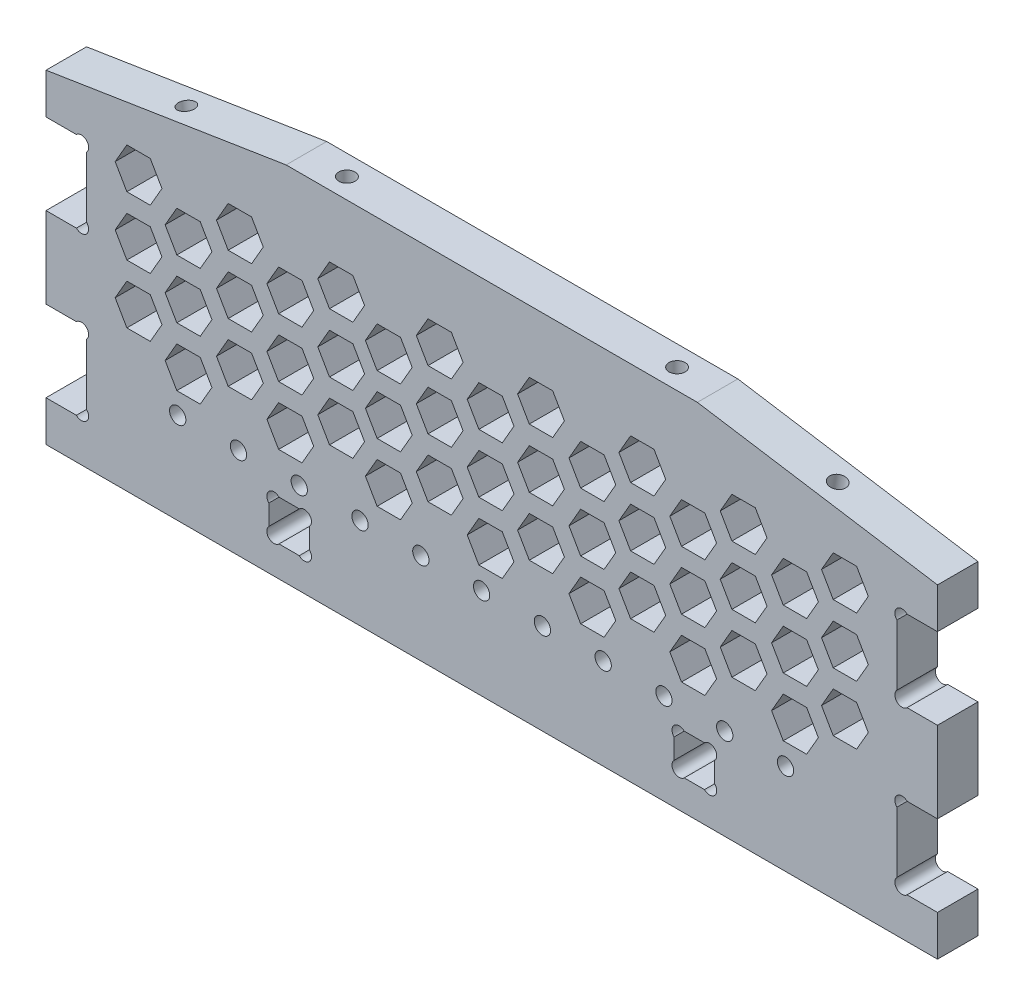
SolidWorks part; units mm, degrees
material "6061 Alloy"
ref_plane "Front" through (0, 0, 0) normal (0, 0, 1) x (1, 0, 0)
ref_plane "Top" through (0, 0, 0) normal (0, 1, 0) x (1, 0, 0)
ref_plane "Right" through (0, 0, 0) normal (1, 0, 0) x (0, 0, -1)
sketch "Sketch2" plane through (0, 0, 0) normal (0, 0, 1) x (1, 0, 0)
  line L1 (-139.7, -50.8) -> (139.7, -50.8)
  line L2 (-139.7, -50.8) -> (-139.7, 50.8)
  line L3 (-139.7, 50.8) -> (139.7, 50.8)
  line L4 (139.7, -50.8) -> (139.7, 50.8)
  line L5 (-139.7, -50.8) -> (139.7, 50.8) construction
  line L6 (-139.7, 50.8) -> (139.7, -50.8) construction
  point P0 (0, 0)
  dimension "D1" = 279.4
  dimension "D2" = 101.6
extrude "Rectangle Extrusion" add sketch "Sketch2" along normal blind 12.7
sketch "Sketch3" plane through (0, 0, 0) normal (0, 0, -1) x (-1, 0, 0)
  line L0 (-139.7, -50.8) -> (-63.5, -50.8) construction
  line L1 (139.7, -50.8) -> (-139.7, -50.8) construction
  line L2 (-63.5, -50.8) -> (-63.5, -34.925) construction
  line L3 (0, 6.985) -> (0, -6.985) construction
  line L4 (-69.85, -41.275) -> (-57.15, -41.275)
  line L5 (-69.85, -41.275) -> (-69.85, -28.575)
  line L6 (-69.85, -28.575) -> (-57.15, -28.575)
  line L7 (-57.15, -41.275) -> (-57.15, -28.575)
  line L8 (-69.85, -41.275) -> (-57.15, -28.575) construction
  line L9 (-69.85, -28.575) -> (-57.15, -41.275) construction
  line L10 (69.85, -28.575) -> (57.15, -28.575)
  line L11 (57.15, -41.275) -> (57.15, -28.575)
  line L12 (69.85, -41.275) -> (57.15, -41.275)
  line L13 (69.85, -41.275) -> (69.85, -28.575)
  line L14 (-69.85, -34.925) -> (-57.15, -34.925) construction
  circle A0 centre (-68.2625, -30.1625) radius 2.2454
  circle A1 centre (-58.7375, -30.1625) radius 2.2454
  circle A2 centre (-58.7375, -39.6875) radius 2.2454
  circle A3 centre (-68.2625, -39.6875) radius 2.2454
  circle A4 centre (58.7375, -39.6875) radius 2.2454
  circle A5 centre (68.2625, -39.6875) radius 2.2454
  circle A6 centre (58.7375, -30.1625) radius 2.2454
  circle A7 centre (68.2625, -30.1625) radius 2.2454
  dimension "D5" = 1.5875
  dimension "D6" = 4.4907
  dimension "D1" = 76.2
  dimension "D2" = 9.525
  dimension "D3" = 12.7
  dimension "D4" = 12.7
extrude "Slotting Holes" cut sketch "Sketch3" against normal up to surface (12.7 mm away) contours L6 A0 L5 | L5 A3 L4 A2 L7 A1 L6 A0 | L5 A0 L6 | A1 L7 L6 | A1 L6 L7 | L7 A2 L4 | L4 A2 L7 | A3 L5 L4 | A3 L4 L5 | L10 A6 L11 | L11 A6 L10 | L13 A7 L10 A6 L11 A4 L12 A5 | A7 L13 L10 | A7 L10 L13 | L12 A5 L13 | A4 L12 L11 | L13 A5 L12 | A4 L11 L12 up to face at (0, 0, 12.7)
sketch "Sketch4" plane through (0, 0, 12.7) normal (0, 0, 1) x (1, 0, 0)
  line L0 (0, -11.43) -> (0, 0) construction
  line L1 (6.9677, 27.5012) -> (3.3015, 33.8512)
  line L2 (-24.9281, 27.5012) -> (-28.5942, 33.8512)
  line L3 (-28.5942, 33.8512) -> (-35.9266, 33.8512)
  line L4 (-35.9266, 33.8512) -> (-39.5928, 27.5012)
  line L5 (-39.5928, 27.5012) -> (-35.9266, 21.1512)
  line L6 (-35.9266, 21.1512) -> (-28.5942, 21.1512)
  line L7 (-28.5942, 21.1512) -> (-24.9281, 27.5012)
  line L8 (3.3015, 33.8512) -> (-4.0309, 33.8512)
  line L9 (-4.0309, 33.8512) -> (-7.697, 27.5012)
  line L10 (-7.697, 27.5012) -> (-4.0309, 21.1512)
  line L11 (-4.0309, 21.1512) -> (3.3015, 21.1512)
  line L12 (3.3015, 21.1512) -> (6.9677, 27.5012)
  line L13 (38.8634, 27.5012) -> (35.1972, 33.8512)
  line L14 (35.1972, 33.8512) -> (27.8648, 33.8512)
  line L15 (27.8648, 33.8512) -> (24.1987, 27.5012)
  line L16 (24.1987, 27.5012) -> (27.8648, 21.1512)
  line L17 (27.8648, 21.1512) -> (35.1972, 21.1512)
  line L18 (35.1972, 21.1512) -> (38.8634, 27.5012)
  line L19 (-8.9802, 18.2937) -> (-12.6464, 24.6437)
  line L20 (-12.6464, 24.6437) -> (-19.9787, 24.6437)
  line L21 (-19.9787, 24.6437) -> (-23.6449, 18.2937)
  line L22 (-23.6449, 18.2937) -> (-19.9787, 11.9437)
  line L23 (-19.9787, 11.9437) -> (-12.6464, 11.9437)
  line L24 (-12.6464, 11.9437) -> (-8.9802, 18.2937)
  line L25 (22.7698, 18.2937) -> (19.1036, 24.6437)
  line L26 (19.1036, 24.6437) -> (11.7713, 24.6437)
  line L27 (11.7713, 24.6437) -> (8.1051, 18.2937)
  line L28 (8.1051, 18.2937) -> (11.7713, 11.9437)
  line L29 (11.7713, 11.9437) -> (19.1036, 11.9437)
  line L30 (19.1036, 11.9437) -> (22.7698, 18.2937)
  line L31 (-24.9281, 9.0862) -> (-28.5942, 15.4362)
  line L32 (-28.5942, 15.4362) -> (-35.9266, 15.4362)
  line L33 (-35.9266, 15.4362) -> (-39.5928, 9.0862)
  line L34 (-39.5928, 9.0862) -> (-35.9266, 2.7362)
  line L35 (-35.9266, 2.7362) -> (-28.5942, 2.7362)
  line L36 (-28.5942, 2.7362) -> (-24.9281, 9.0862)
  line L37 (6.9677, 9.0862) -> (3.3015, 15.4362)
  line L38 (3.3015, 15.4362) -> (-4.0309, 15.4362)
  line L39 (-4.0309, 15.4362) -> (-7.697, 9.0862)
  line L40 (-7.697, 9.0862) -> (-4.0309, 2.7362)
  line L41 (-4.0309, 2.7362) -> (3.3015, 2.7362)
  line L42 (3.3015, 2.7362) -> (6.9677, 9.0862)
  line L43 (38.8634, 9.0862) -> (35.1972, 15.4362)
  line L44 (35.1972, 15.4362) -> (27.8648, 15.4362)
  line L45 (27.8648, 15.4362) -> (24.1987, 9.0862)
  line L46 (24.1987, 9.0862) -> (27.8648, 2.7362)
  line L47 (27.8648, 2.7362) -> (35.1972, 2.7362)
  line L48 (35.1972, 2.7362) -> (38.8634, 9.0862)
  line L49 (-24.9281, -9.3288) -> (-28.5942, -2.9788)
  line L50 (-28.5942, -2.9788) -> (-35.9266, -2.9788)
  line L51 (-35.9266, -2.9788) -> (-39.5928, -9.3288)
  line L52 (-39.5928, -9.3288) -> (-35.9266, -15.6788)
  line L53 (-35.9266, -15.6788) -> (-28.5942, -15.6788)
  line L54 (-28.5942, -15.6788) -> (-24.9281, -9.3288)
  line L55 (-8.9802, -18.5363) -> (-12.6464, -12.1863)
  line L56 (-12.6464, -12.1863) -> (-19.9787, -12.1863)
  line L57 (-19.9787, -12.1863) -> (-23.6449, -18.5363)
  line L58 (-23.6449, -18.5363) -> (-19.9787, -24.8863)
  line L59 (-19.9787, -24.8863) -> (-12.6464, -24.8863)
  line L60 (-12.6464, -24.8863) -> (-8.9802, -18.5363)
  line L61 (6.9677, -9.3288) -> (3.3015, -2.9788)
  line L62 (3.3015, -2.9788) -> (-4.0309, -2.9788)
  line L63 (-4.0309, -2.9788) -> (-7.697, -9.3288)
  line L64 (-7.697, -9.3288) -> (-4.0309, -15.6788)
  line L65 (-4.0309, -15.6788) -> (3.3015, -15.6788)
  line L66 (3.3015, -15.6788) -> (6.9677, -9.3288)
  line L67 (22.7698, -18.5363) -> (19.1036, -12.1863)
  line L68 (19.1036, -12.1863) -> (11.7713, -12.1863)
  line L69 (11.7713, -12.1863) -> (8.1051, -18.5363)
  line L70 (8.1051, -18.5363) -> (11.7713, -24.8863)
  line L71 (11.7713, -24.8863) -> (19.1036, -24.8863)
  line L72 (19.1036, -24.8863) -> (22.7698, -18.5363)
  line L73 (38.8634, -9.3288) -> (35.1972, -2.9788)
  line L74 (35.1972, -2.9788) -> (27.8648, -2.9788)
  line L75 (27.8648, -2.9788) -> (24.1987, -9.3288)
  line L76 (24.1987, -9.3288) -> (27.8648, -15.6788)
  line L77 (27.8648, -15.6788) -> (35.1972, -15.6788)
  line L78 (35.1972, -15.6788) -> (38.8634, -9.3288)
  line L79 (38.8634, -27.7438) -> (35.1972, -21.3938)
  line L80 (35.1972, -21.3938) -> (27.8648, -21.3938)
  line L81 (27.8648, -21.3938) -> (24.1987, -27.7438)
  line L82 (24.1987, -27.7438) -> (27.8648, -34.0938)
  line L83 (27.8648, -34.0938) -> (35.1972, -34.0938)
  line L84 (35.1972, -34.0938) -> (38.8634, -27.7438)
  line L85 (6.9677, -27.7438) -> (3.3015, -21.3938)
  line L86 (-4.0309, -21.3938) -> (-7.697, -27.7438)
  line L87 (-7.697, -27.7438) -> (-4.0309, -34.0938)
  line L88 (-4.0309, -34.0938) -> (3.3015, -34.0938)
  line L89 (3.3015, -34.0938) -> (6.9677, -27.7438)
  line L90 (3.3015, -21.3938) -> (-4.0309, -21.3938)
  line L91 (-24.9281, -27.7438) -> (-28.5942, -21.3938)
  line L92 (-28.5942, -21.3938) -> (-35.9266, -21.3938)
  line L93 (-35.9266, -21.3938) -> (-39.5928, -27.7438)
  line L94 (-39.5928, -27.7438) -> (-35.9266, -34.0938)
  line L95 (-35.9266, -34.0938) -> (-28.5942, -34.0938)
  line L96 (-28.5942, -34.0938) -> (-24.9281, -27.7438)
  line L97 (22.7698, -0.1213) -> (19.1036, 6.2287)
  line L98 (19.1036, 6.2287) -> (11.7713, 6.2287)
  line L99 (11.7713, 6.2287) -> (8.1051, -0.1213)
  line L100 (8.1051, -0.1213) -> (11.7713, -6.4713)
  line L101 (11.7713, -6.4713) -> (19.1036, -6.4713)
  line L102 (19.1036, -6.4713) -> (22.7698, -0.1213)
  line L103 (-8.9802, -0.1213) -> (-12.6464, 6.2287)
  line L104 (-12.6464, 6.2287) -> (-19.9787, 6.2287)
  line L105 (-19.9787, 6.2287) -> (-23.6449, -0.1213)
  line L106 (-23.6449, -0.1213) -> (-19.9787, -6.4713)
  line L107 (-19.9787, -6.4713) -> (-12.6464, -6.4713)
  line L108 (-12.6464, -6.4713) -> (-8.9802, -0.1213)
  line L109 (-8.9802, -37.0783) -> (-12.6464, -30.7283)
  line L110 (-12.6464, -30.7283) -> (-19.9787, -30.7283)
  line L111 (-19.9787, -30.7283) -> (-23.6449, -37.0783)
  line L112 (-23.6449, -37.0783) -> (-19.9787, -43.4283)
  line L113 (-19.9787, -43.4283) -> (-12.6464, -43.4283)
  line L114 (-12.6464, -43.4283) -> (-8.9802, -37.0783)
  line L115 (22.7698, -37.0783) -> (19.1036, -30.7283)
  line L116 (19.1036, -30.7283) -> (11.7713, -30.7283)
  line L117 (11.7713, -30.7283) -> (8.1051, -37.0783)
  line L118 (8.1051, -37.0783) -> (11.7713, -43.4283)
  line L119 (11.7713, -43.4283) -> (19.1036, -43.4283)
  line L120 (19.1036, -43.4283) -> (22.7698, -37.0783)
  line L121 (-8.9802, 36.8357) -> (-12.6464, 43.1857)
  line L122 (-12.6464, 43.1857) -> (-19.9787, 43.1857)
  line L123 (-19.9787, 43.1857) -> (-23.6449, 36.8357)
  line L124 (-23.6449, 36.8357) -> (-19.9787, 30.4857)
  line L125 (-19.9787, 30.4857) -> (-12.6464, 30.4857)
  line L126 (-12.6464, 30.4857) -> (-8.9802, 36.8357)
  line L127 (22.7698, 36.8357) -> (19.1036, 43.1857)
  line L128 (19.1036, 43.1857) -> (11.7713, 43.1857)
  line L129 (11.7713, 43.1857) -> (8.1051, 36.8357)
  line L130 (8.1051, 36.8357) -> (11.7713, 30.4857)
  line L131 (11.7713, 30.4857) -> (19.1036, 30.4857)
  line L132 (19.1036, 30.4857) -> (22.7698, 36.8357)
  line L133 (63.5, -11.43) -> (63.5, 0) construction
  line L134 (70.4677, 27.5012) -> (66.8015, 33.8512)
  line L141 (66.8015, 33.8512) -> (59.4691, 33.8512)
  line L142 (59.4691, 33.8512) -> (55.803, 27.5012)
  line L143 (55.803, 27.5012) -> (59.4691, 21.1512)
  line L144 (59.4691, 21.1512) -> (66.8015, 21.1512)
  line L145 (66.8015, 21.1512) -> (70.4677, 27.5012)
  line L146 (102.3634, 27.5012) -> (98.6972, 33.8512)
  line L147 (98.6972, 33.8512) -> (91.3648, 33.8512)
  line L148 (91.3648, 33.8512) -> (87.6987, 27.5012)
  line L149 (87.6987, 27.5012) -> (91.3648, 21.1512)
  line L150 (91.3648, 21.1512) -> (98.6972, 21.1512)
  line L151 (98.6972, 21.1512) -> (102.3634, 27.5012)
  line L152 (54.5198, 18.2937) -> (50.8536, 24.6437)
  line L153 (50.8536, 24.6437) -> (43.5213, 24.6437)
  line L154 (43.5213, 24.6437) -> (39.8551, 18.2937)
  line L155 (39.8551, 18.2937) -> (43.5213, 11.9437)
  line L156 (43.5213, 11.9437) -> (50.8536, 11.9437)
  line L157 (50.8536, 11.9437) -> (54.5198, 18.2937)
  line L158 (86.2698, 18.2937) -> (82.6036, 24.6437)
  line L159 (82.6036, 24.6437) -> (75.2713, 24.6437)
  line L160 (75.2713, 24.6437) -> (71.6051, 18.2937)
  line L161 (71.6051, 18.2937) -> (75.2713, 11.9437)
  line L162 (75.2713, 11.9437) -> (82.6036, 11.9437)
  line L163 (82.6036, 11.9437) -> (86.2698, 18.2937)
  line L170 (70.4677, 9.0862) -> (66.8015, 15.4362)
  line L171 (66.8015, 15.4362) -> (59.4691, 15.4362)
  line L172 (59.4691, 15.4362) -> (55.803, 9.0862)
  line L173 (55.803, 9.0862) -> (59.4691, 2.7362)
  line L174 (59.4691, 2.7362) -> (66.8015, 2.7362)
  line L175 (66.8015, 2.7362) -> (70.4677, 9.0862)
  line L176 (102.3634, 9.0862) -> (98.6972, 15.4362)
  line L177 (98.6972, 15.4362) -> (91.3648, 15.4362)
  line L178 (91.3648, 15.4362) -> (87.6987, 9.0862)
  line L179 (87.6987, 9.0862) -> (91.3648, 2.7362)
  line L180 (91.3648, 2.7362) -> (98.6972, 2.7362)
  line L181 (98.6972, 2.7362) -> (102.3634, 9.0862)
  line L188 (54.5198, -18.5363) -> (50.8536, -12.1863)
  line L189 (50.8536, -12.1863) -> (43.5213, -12.1863)
  line L190 (43.5213, -12.1863) -> (39.8551, -18.5363)
  line L191 (39.8551, -18.5363) -> (43.5213, -24.8863)
  line L192 (43.5213, -24.8863) -> (50.8536, -24.8863)
  line L193 (50.8536, -24.8863) -> (54.5198, -18.5363)
  line L194 (70.4677, -9.3288) -> (66.8015, -2.9788)
  line L195 (66.8015, -2.9788) -> (59.4691, -2.9788)
  line L196 (59.4691, -2.9788) -> (55.803, -9.3288)
  line L197 (55.803, -9.3288) -> (59.4691, -15.6788)
  line L198 (59.4691, -15.6788) -> (66.8015, -15.6788)
  line L199 (66.8015, -15.6788) -> (70.4677, -9.3288)
  line L200 (86.2698, -18.5363) -> (82.6036, -12.1863)
  line L201 (82.6036, -12.1863) -> (75.2713, -12.1863)
  line L202 (75.2713, -12.1863) -> (71.6051, -18.5363)
  line L203 (71.6051, -18.5363) -> (75.2713, -24.8863)
  line L204 (75.2713, -24.8863) -> (82.6036, -24.8863)
  line L205 (82.6036, -24.8863) -> (86.2698, -18.5363)
  line L206 (102.3634, -9.3288) -> (98.6972, -2.9788)
  line L207 (98.6972, -2.9788) -> (91.3648, -2.9788)
  line L208 (91.3648, -2.9788) -> (87.6987, -9.3288)
  line L209 (87.6987, -9.3288) -> (91.3648, -15.6788)
  line L210 (91.3648, -15.6788) -> (98.6972, -15.6788)
  line L211 (98.6972, -15.6788) -> (102.3634, -9.3288)
  line L212 (102.3634, -27.7438) -> (98.6972, -21.3938)
  line L213 (98.6972, -21.3938) -> (91.3648, -21.3938)
  line L214 (91.3648, -21.3938) -> (87.6987, -27.7438)
  line L215 (87.6987, -27.7438) -> (91.3648, -34.0938)
  line L216 (91.3648, -34.0938) -> (98.6972, -34.0938)
  line L217 (98.6972, -34.0938) -> (102.3634, -27.7438)
  line L230 (86.2698, -0.1213) -> (82.6036, 6.2287)
  line L231 (82.6036, 6.2287) -> (75.2713, 6.2287)
  line L232 (75.2713, 6.2287) -> (71.6051, -0.1213)
  line L233 (71.6051, -0.1213) -> (75.2713, -6.4713)
  line L234 (75.2713, -6.4713) -> (82.6036, -6.4713)
  line L235 (82.6036, -6.4713) -> (86.2698, -0.1213)
  line L236 (54.5198, -0.1213) -> (50.8536, 6.2287)
  line L237 (50.8536, 6.2287) -> (43.5213, 6.2287)
  line L238 (43.5213, 6.2287) -> (39.8551, -0.1213)
  line L239 (39.8551, -0.1213) -> (43.5213, -6.4713)
  line L240 (43.5213, -6.4713) -> (50.8536, -6.4713)
  line L241 (50.8536, -6.4713) -> (54.5198, -0.1213)
  line L254 (54.5198, 36.8357) -> (50.8536, 43.1857)
  line L255 (50.8536, 43.1857) -> (43.5213, 43.1857)
  line L256 (43.5213, 43.1857) -> (39.8551, 36.8357)
  line L257 (39.8551, 36.8357) -> (43.5213, 30.4857)
  line L258 (43.5213, 30.4857) -> (50.8536, 30.4857)
  line L259 (50.8536, 30.4857) -> (54.5198, 36.8357)
  line L260 (86.2698, 36.8357) -> (82.6036, 43.1857)
  line L261 (82.6036, 43.1857) -> (75.2713, 43.1857)
  line L262 (75.2713, 43.1857) -> (71.6051, 36.8357)
  line L263 (71.6051, 36.8357) -> (75.2713, 30.4857)
  line L264 (75.2713, 30.4857) -> (82.6036, 30.4857)
  line L265 (82.6036, 30.4857) -> (86.2698, 36.8357)
  line L266 (118.0198, 36.8357) -> (114.3536, 43.1857)
  line L267 (114.3536, 43.1857) -> (107.0213, 43.1857)
  line L268 (107.0213, 43.1857) -> (103.3551, 36.8357)
  line L269 (103.3551, 36.8357) -> (107.0213, 30.4857)
  line L270 (107.0213, 30.4857) -> (114.3536, 30.4857)
  line L271 (114.3536, 30.4857) -> (118.0198, 36.8357)
  line L272 (118.0198, 18.2937) -> (114.3536, 24.6437)
  line L273 (114.3536, 24.6437) -> (107.0213, 24.6437)
  line L274 (107.0213, 24.6437) -> (103.3551, 18.2937)
  line L275 (103.3551, 18.2937) -> (107.0213, 11.9437)
  line L276 (107.0213, 11.9437) -> (114.3536, 11.9437)
  line L277 (114.3536, 11.9437) -> (118.0198, 18.2937)
  line L278 (118.0198, -0.1213) -> (114.3536, 6.2287)
  line L279 (114.3536, 6.2287) -> (107.0213, 6.2287)
  line L280 (107.0213, 6.2287) -> (103.3551, -0.1213)
  line L281 (103.3551, -0.1213) -> (107.0213, -6.4713)
  line L282 (107.0213, -6.4713) -> (114.3536, -6.4713)
  line L283 (114.3536, -6.4713) -> (118.0198, -0.1213)
  line L284 (118.0198, -18.5363) -> (114.3536, -12.1863)
  line L285 (114.3536, -12.1863) -> (107.0213, -12.1863)
  line L286 (107.0213, -12.1863) -> (103.3551, -18.5363)
  line L287 (103.3551, -18.5363) -> (107.0213, -24.8863)
  line L288 (107.0213, -24.8863) -> (114.3536, -24.8863)
  line L289 (114.3536, -24.8863) -> (118.0198, -18.5363)
  line L290 (117.8959, -37.2022) -> (114.2298, -30.8522)
  line L291 (114.2298, -30.8522) -> (106.8974, -30.8522)
  line L292 (106.8974, -30.8522) -> (103.2312, -37.2022)
  line L293 (103.2312, -37.2022) -> (106.8974, -43.5522)
  line L294 (106.8974, -43.5522) -> (114.2298, -43.5522)
  line L295 (114.2298, -43.5522) -> (117.8959, -37.2022)
  line L296 (0, -6.985) -> (0, 6.985) construction
  line L297 (-63.5, -11.43) -> (-63.5, 0) construction
  line L298 (-114.2298, -43.5522) -> (-117.8959, -37.2022)
  line L299 (-106.8974, -43.5522) -> (-114.2298, -43.5522)
  line L300 (-103.2312, -37.2022) -> (-106.8974, -43.5522)
  line L301 (-106.8974, -30.8522) -> (-103.2312, -37.2022)
  line L302 (-114.2298, -30.8522) -> (-106.8974, -30.8522)
  line L303 (-117.8959, -37.2022) -> (-114.2298, -30.8522)
  line L304 (-114.3536, -24.8863) -> (-118.0198, -18.5363)
  line L305 (-107.0213, -24.8863) -> (-114.3536, -24.8863)
  line L306 (-103.3551, -18.5363) -> (-107.0213, -24.8863)
  line L307 (-107.0213, -12.1863) -> (-103.3551, -18.5363)
  line L308 (-114.3536, -12.1863) -> (-107.0213, -12.1863)
  line L309 (-118.0198, -18.5363) -> (-114.3536, -12.1863)
  line L310 (-114.3536, -6.4713) -> (-118.0198, -0.1213)
  line L311 (-107.0213, -6.4713) -> (-114.3536, -6.4713)
  line L312 (-103.3551, -0.1213) -> (-107.0213, -6.4713)
  line L313 (-107.0213, 6.2287) -> (-103.3551, -0.1213)
  line L314 (-114.3536, 6.2287) -> (-107.0213, 6.2287)
  line L315 (-118.0198, -0.1213) -> (-114.3536, 6.2287)
  line L316 (-114.3536, 11.9437) -> (-118.0198, 18.2937)
  line L317 (-107.0213, 11.9437) -> (-114.3536, 11.9437)
  line L318 (-103.3551, 18.2937) -> (-107.0213, 11.9437)
  line L319 (-107.0213, 24.6437) -> (-103.3551, 18.2937)
  line L320 (-114.3536, 24.6437) -> (-107.0213, 24.6437)
  line L321 (-118.0198, 18.2937) -> (-114.3536, 24.6437)
  line L322 (-114.3536, 30.4857) -> (-118.0198, 36.8357)
  line L323 (-107.0213, 30.4857) -> (-114.3536, 30.4857)
  line L324 (-103.3551, 36.8357) -> (-107.0213, 30.4857)
  line L325 (-107.0213, 43.1857) -> (-103.3551, 36.8357)
  line L326 (-114.3536, 43.1857) -> (-107.0213, 43.1857)
  line L327 (-118.0198, 36.8357) -> (-114.3536, 43.1857)
  line L328 (-82.6036, 30.4857) -> (-86.2698, 36.8357)
  line L329 (-75.2713, 30.4857) -> (-82.6036, 30.4857)
  line L330 (-71.6051, 36.8357) -> (-75.2713, 30.4857)
  line L331 (-75.2713, 43.1857) -> (-71.6051, 36.8357)
  line L332 (-82.6036, 43.1857) -> (-75.2713, 43.1857)
  line L333 (-86.2698, 36.8357) -> (-82.6036, 43.1857)
  line L334 (-50.8536, 30.4857) -> (-54.5198, 36.8357)
  line L335 (-43.5213, 30.4857) -> (-50.8536, 30.4857)
  line L336 (-39.8551, 36.8357) -> (-43.5213, 30.4857)
  line L337 (-43.5213, 43.1857) -> (-39.8551, 36.8357)
  line L338 (-50.8536, 43.1857) -> (-43.5213, 43.1857)
  line L339 (-54.5198, 36.8357) -> (-50.8536, 43.1857)
  line L346 (-50.8536, -6.4713) -> (-54.5198, -0.1213)
  line L347 (-43.5213, -6.4713) -> (-50.8536, -6.4713)
  line L348 (-39.8551, -0.1213) -> (-43.5213, -6.4713)
  line L349 (-43.5213, 6.2287) -> (-39.8551, -0.1213)
  line L350 (-50.8536, 6.2287) -> (-43.5213, 6.2287)
  line L351 (-54.5198, -0.1213) -> (-50.8536, 6.2287)
  line L352 (-82.6036, -6.4713) -> (-86.2698, -0.1213)
  line L353 (-75.2713, -6.4713) -> (-82.6036, -6.4713)
  line L354 (-71.6051, -0.1213) -> (-75.2713, -6.4713)
  line L355 (-75.2713, 6.2287) -> (-71.6051, -0.1213)
  line L356 (-82.6036, 6.2287) -> (-75.2713, 6.2287)
  line L357 (-86.2698, -0.1213) -> (-82.6036, 6.2287)
  line L358 (-98.6972, -34.0938) -> (-102.3634, -27.7438)
  line L359 (-91.3648, -34.0938) -> (-98.6972, -34.0938)
  line L360 (-87.6987, -27.7438) -> (-91.3648, -34.0938)
  line L361 (-91.3648, -21.3938) -> (-87.6987, -27.7438)
  line L362 (-98.6972, -21.3938) -> (-91.3648, -21.3938)
  line L363 (-102.3634, -27.7438) -> (-98.6972, -21.3938)
  line L364 (-98.6972, -15.6788) -> (-102.3634, -9.3288)
  line L365 (-91.3648, -15.6788) -> (-98.6972, -15.6788)
  line L366 (-87.6987, -9.3288) -> (-91.3648, -15.6788)
  line L367 (-91.3648, -2.9788) -> (-87.6987, -9.3288)
  line L368 (-98.6972, -2.9788) -> (-91.3648, -2.9788)
  line L369 (-102.3634, -9.3288) -> (-98.6972, -2.9788)
  line L370 (-82.6036, -24.8863) -> (-86.2698, -18.5363)
  line L371 (-75.2713, -24.8863) -> (-82.6036, -24.8863)
  line L372 (-71.6051, -18.5363) -> (-75.2713, -24.8863)
  line L373 (-75.2713, -12.1863) -> (-71.6051, -18.5363)
  line L374 (-82.6036, -12.1863) -> (-75.2713, -12.1863)
  line L375 (-86.2698, -18.5363) -> (-82.6036, -12.1863)
  line L376 (-66.8015, -15.6788) -> (-70.4677, -9.3288)
  line L377 (-59.4691, -15.6788) -> (-66.8015, -15.6788)
  line L378 (-55.803, -9.3288) -> (-59.4691, -15.6788)
  line L379 (-59.4691, -2.9788) -> (-55.803, -9.3288)
  line L380 (-66.8015, -2.9788) -> (-59.4691, -2.9788)
  line L381 (-70.4677, -9.3288) -> (-66.8015, -2.9788)
  line L382 (-50.8536, -24.8863) -> (-54.5198, -18.5363)
  line L383 (-43.5213, -24.8863) -> (-50.8536, -24.8863)
  line L384 (-39.8551, -18.5363) -> (-43.5213, -24.8863)
  line L385 (-43.5213, -12.1863) -> (-39.8551, -18.5363)
  line L386 (-50.8536, -12.1863) -> (-43.5213, -12.1863)
  line L387 (-54.5198, -18.5363) -> (-50.8536, -12.1863)
  line L388 (-98.6972, 2.7362) -> (-102.3634, 9.0862)
  line L389 (-91.3648, 2.7362) -> (-98.6972, 2.7362)
  line L390 (-87.6987, 9.0862) -> (-91.3648, 2.7362)
  line L391 (-91.3648, 15.4362) -> (-87.6987, 9.0862)
  line L392 (-98.6972, 15.4362) -> (-91.3648, 15.4362)
  line L393 (-102.3634, 9.0862) -> (-98.6972, 15.4362)
  line L394 (-66.8015, 2.7362) -> (-70.4677, 9.0862)
  line L395 (-59.4691, 2.7362) -> (-66.8015, 2.7362)
  line L396 (-55.803, 9.0862) -> (-59.4691, 2.7362)
  line L397 (-59.4691, 15.4362) -> (-55.803, 9.0862)
  line L398 (-66.8015, 15.4362) -> (-59.4691, 15.4362)
  line L399 (-70.4677, 9.0862) -> (-66.8015, 15.4362)
  line L400 (-82.6036, 11.9437) -> (-86.2698, 18.2937)
  line L401 (-75.2713, 11.9437) -> (-82.6036, 11.9437)
  line L402 (-71.6051, 18.2937) -> (-75.2713, 11.9437)
  line L403 (-75.2713, 24.6437) -> (-71.6051, 18.2937)
  line L404 (-82.6036, 24.6437) -> (-75.2713, 24.6437)
  line L405 (-86.2698, 18.2937) -> (-82.6036, 24.6437)
  line L406 (-50.8536, 11.9437) -> (-54.5198, 18.2937)
  line L407 (-43.5213, 11.9437) -> (-50.8536, 11.9437)
  line L408 (-39.8551, 18.2937) -> (-43.5213, 11.9437)
  line L409 (-43.5213, 24.6437) -> (-39.8551, 18.2937)
  line L410 (-50.8536, 24.6437) -> (-43.5213, 24.6437)
  line L411 (-54.5198, 18.2937) -> (-50.8536, 24.6437)
  line L412 (-98.6972, 21.1512) -> (-102.3634, 27.5012)
  line L413 (-91.3648, 21.1512) -> (-98.6972, 21.1512)
  line L414 (-87.6987, 27.5012) -> (-91.3648, 21.1512)
  line L415 (-91.3648, 33.8512) -> (-87.6987, 27.5012)
  line L416 (-98.6972, 33.8512) -> (-91.3648, 33.8512)
  line L417 (-102.3634, 27.5012) -> (-98.6972, 33.8512)
  line L418 (-66.8015, 21.1512) -> (-70.4677, 27.5012)
  line L419 (-59.4691, 21.1512) -> (-66.8015, 21.1512)
  line L420 (-55.803, 27.5012) -> (-59.4691, 21.1512)
  line L421 (-59.4691, 33.8512) -> (-55.803, 27.5012)
  line L422 (-66.8015, 33.8512) -> (-59.4691, 33.8512)
  line L423 (-70.4677, 27.5012) -> (-66.8015, 33.8512)
  circle A0 centre (-32.2604, 27.5012) radius 6.35 construction
  circle A1 centre (-0.3647, 27.5012) radius 6.35 construction
  circle A2 centre (31.531, 27.5012) radius 6.35 construction
  circle A3 centre (-16.3126, 18.2937) radius 6.35 construction
  circle A4 centre (15.4374, 18.2937) radius 6.35 construction
  circle A5 centre (-32.2604, 9.0862) radius 6.35 construction
  circle A6 centre (-0.3647, 9.0862) radius 6.35 construction
  circle A7 centre (31.531, 9.0862) radius 6.35 construction
  circle A8 centre (-32.2604, -9.3288) radius 6.35 construction
  circle A9 centre (-16.3126, -18.5363) radius 6.35 construction
  circle A10 centre (-0.3647, -9.3288) radius 6.35 construction
  circle A11 centre (15.4374, -18.5363) radius 6.35 construction
  circle A12 centre (31.531, -9.3288) radius 6.35 construction
  circle A13 centre (31.531, -27.7438) radius 6.35 construction
  circle A14 centre (-0.3647, -27.7438) radius 6.35 construction
  circle A15 centre (-32.2604, -27.7438) radius 6.35 construction
  circle A16 centre (-16.3126, -0.1213) radius 6.35 construction
  circle A17 centre (15.4374, -0.1213) radius 6.35 construction
  circle A18 centre (-16.3126, -37.0783) radius 6.35 construction
  circle A19 centre (15.4374, -37.0783) radius 6.35 construction
  circle A20 centre (-16.3126, 36.8357) radius 6.35 construction
  circle A21 centre (15.4374, 36.8357) radius 6.35 construction
  circle A23 centre (63.1353, 27.5012) radius 6.35 construction
  circle A24 centre (95.031, 27.5012) radius 6.35 construction
  circle A25 centre (47.1874, 18.2937) radius 6.35 construction
  circle A26 centre (78.9374, 18.2937) radius 6.35 construction
  circle A28 centre (63.1353, 9.0862) radius 6.35 construction
  circle A29 centre (95.031, 9.0862) radius 6.35 construction
  circle A31 centre (47.1874, -18.5363) radius 6.35 construction
  circle A32 centre (63.1353, -9.3288) radius 6.35 construction
  circle A33 centre (78.9374, -18.5363) radius 6.35 construction
  circle A34 centre (95.031, -9.3288) radius 6.35 construction
  circle A35 centre (95.031, -27.7438) radius 6.35 construction
  circle A38 centre (47.1874, -0.1213) radius 6.35 construction
  circle A39 centre (78.9374, -0.1213) radius 6.35 construction
  circle A42 centre (47.1874, 36.8357) radius 6.35 construction
  circle A43 centre (78.9374, 36.8357) radius 6.35 construction
  circle A44 centre (110.6874, 36.8357) radius 6.35 construction
  circle A45 centre (110.6874, 18.2937) radius 6.35 construction
  circle A46 centre (110.6874, -0.1213) radius 6.35 construction
  circle A47 centre (110.6874, -18.5363) radius 6.35 construction
  circle A48 centre (110.6874, -37.0783) radius 6.35 construction
  circle A49 centre (-110.6874, -37.0783) radius 6.35 construction
  circle A50 centre (-110.6874, -18.5363) radius 6.35 construction
  circle A51 centre (-110.6874, -0.1213) radius 6.35 construction
  circle A52 centre (-110.6874, 18.2937) radius 6.35 construction
  circle A53 centre (-110.6874, 36.8357) radius 6.35 construction
  circle A54 centre (-78.9374, 36.8357) radius 6.35 construction
  circle A55 centre (-47.1874, 36.8357) radius 6.35 construction
  circle A57 centre (-78.9374, -0.1213) radius 6.35 construction
  circle A58 centre (-47.1874, -0.1213) radius 6.35 construction
  circle A59 centre (-95.031, -27.7438) radius 6.35 construction
  circle A60 centre (-95.031, -9.3288) radius 6.35 construction
  circle A61 centre (-78.9374, -18.5363) radius 6.35 construction
  circle A62 centre (-63.1353, -9.3288) radius 6.35 construction
  circle A63 centre (-47.1874, -18.5363) radius 6.35 construction
  circle A64 centre (-95.031, 9.0862) radius 6.35 construction
  circle A65 centre (-63.1353, 9.0862) radius 6.35 construction
  circle A66 centre (-78.9374, 18.2937) radius 6.35 construction
  circle A67 centre (-47.1874, 18.2937) radius 6.35 construction
  circle A68 centre (-95.031, 27.5012) radius 6.35 construction
  circle A69 centre (-63.1353, 27.5012) radius 6.35 construction
  dimension "D1" = 11.43
  dimension "D4" = 11.43
  dimension "D5" = 2
  dimension "D2" = 2
  dimension "D3" = 2
extrude "Honeycomb Pocketing" cut sketch "Sketch4" against normal up to surface (12.7 mm away) contours L327 L322 L323 L324 L325 L326 | L333 L328 L329 L330 L331 L332 | L339 L334 L335 L336 L337 L338 | L125 L126 L121 L122 L123 L124 | L131 L132 L127 L128 L129 L130 | L258 L259 L254 L255 L256 L257 | L264 L265 L260 L261 L262 L263 | L270 L271 L266 L267 L268 L269 | L150 L151 L146 L147 L148 L149 | L144 L145 L134 L141 L142 L143 | L17 L18 L13 L14 L15 L16 | L11 L12 L1 L8 L9 L10 | L6 L7 L2 L3 L4 L5 | L423 L418 L419 L420 L421 L422 | L417 L412 L413 L414 L415 L416 | L321 L316 L317 L318 L319 L320 | L405 L400 L401 L402 L403 L404 | L411 L406 L407 L408 L409 L410 | L23 L24 L19 L20 L21 L22 | L29 L30 L25 L26 L27 L28 | L156 L157 L152 L153 L154 L155 | L162 L163 L158 L159 L160 L161 | L276 L277 L272 L273 L274 L275 | L180 L181 L176 L177 L178 L179 | L174 L175 L170 L171 L172 L173 | L47 L48 L43 L44 L45 L46 | L41 L42 L37 L38 L39 L40 | L35 L36 L31 L32 L33 L34 | L399 L394 L395 L396 L397 L398 | L393 L388 L389 L390 L391 L392 | L315 L310 L311 L312 L313 L314 | L357 L352 L353 L354 L355 L356 | L351 L346 L347 L348 L349 L350 | L107 L108 L103 L104 L105 L106 | L101 L102 L97 L98 L99 L100 | L240 L241 L236 L237 L238 L239 | L234 L235 L230 L231 L232 L233 | L282 L283 L278 L279 L280 L281 | L381 L376 L377 L378 L379 L380 | L53 L54 L49 L50 L51 L52 | L369 L364 L365 L366 L367 L368 | L65 L66 L61 L62 L63 L64 | L77 L78 L73 L74 L75 L76 | L198 L199 L194 L195 L196 L197 | L210 L211 L206 L207 L208 L209 up to face at (-63.5, -34.925, 0)
sketch "Sketch5" plane through (0, 0, 12.7) normal (0, 0, 1) x (1, 0, 0)
  line L0 (139.7, 0) -> (139.7, 50.8) construction
  line L1 (139.7, -50.8) -> (139.7, 50.8) construction
  line L2 (139.7, 0) -> (-139.7, 0) construction
  line L4 (139.7, 25.4) -> (139.7, 38.1)
  line L5 (139.7, 38.1) -> (127, 38.1)
  line L6 (127, 25.4) -> (127, 38.1)
  line L8 (127, 25.4) -> (127, 12.7)
  line L9 (127, 12.7) -> (139.7, 12.7)
  line L10 (139.7, 25.4) -> (139.7, 12.7)
  line L11 (-139.7, 50.8) -> (-139.7, -50.8) construction
  line L12 (127, -12.7) -> (139.7, -12.7)
  line L13 (139.7, -25.4) -> (139.7, -12.7)
  line L14 (127, -25.4) -> (139.7, -25.4)
  line L15 (127, -25.4) -> (127, -12.7)
  line L16 (139.7, -38.1) -> (127, -38.1)
  line L17 (127, -25.4) -> (127, -38.1)
  line L18 (139.7, -25.4) -> (127, -25.4)
  line L19 (139.7, -25.4) -> (139.7, -38.1)
  line L20 (0, 50.8) -> (0, -50.8) construction
  line L21 (139.7, 50.8) -> (-139.7, 50.8) construction
  line L22 (-139.7, -50.8) -> (139.7, -50.8) construction
  line L23 (-139.7, -25.4) -> (-139.7, -38.1)
  line L24 (-139.7, -38.1) -> (-127, -38.1)
  line L25 (-127, -25.4) -> (-127, -38.1)
  line L26 (-127, -25.4) -> (-139.7, -25.4)
  line L27 (-139.7, -25.4) -> (-139.7, -12.7)
  line L28 (-127, -12.7) -> (-139.7, -12.7)
  line L29 (-127, -25.4) -> (-127, -12.7)
  line L30 (-139.7, 38.1) -> (-127, 38.1)
  line L31 (-127, 25.4) -> (-127, 38.1)
  line L32 (-139.7, 25.4) -> (-127, 25.4)
  line L33 (-139.7, 25.4) -> (-139.7, 38.1)
  line L34 (-127, 12.7) -> (-139.7, 12.7)
  line L35 (-139.7, 25.4) -> (-139.7, 12.7)
  line L36 (-127, 25.4) -> (-139.7, 25.4)
  line L37 (-127, 25.4) -> (-127, 12.7)
  line L39 (127, 25.4) -> (127, 38.1)
  line L40 (127, 38.1) -> (139.7, 38.1)
  line L41 (139.7, 25.4) -> (139.7, 38.1)
  line L42 (127, 25.4) -> (127.0258, 25.4258) construction
  line L43 (127, 38.1) -> (136.5248, 28.5752) construction
  line L44 (127, 31.75) -> (133.35, 31.75) construction
  line L45 (127, 12.7) -> (139.7, 12.7)
  line L46 (127, 12.7) -> (127, 25.4)
  line L48 (139.7, 12.7) -> (139.7, 25.4)
  line L49 (127, 12.7) -> (130.1752, 15.8752) construction
  line L50 (127, 25.4) -> (127.0258, 25.3742) construction
  line L52 (139.6742, 25.3742) -> (139.7, 25.4) construction
  line L53 (133.35, 19.05) -> (136.5246, 22.2246) construction
  line L54 (130.1752, 22.2248) -> (136.5246, 15.8754) construction
  line L55 (133.35, 31.75) -> (136.5248, 34.9248) construction
  circle A0 centre (128.5875, 36.5125) radius 2.2454
  arc A4 (127.0258, 25.4258) -> (126.9996, 25.4) centre (128.5875, 23.8125) ccw
  circle A7 centre (128.5875, 14.2875) radius 2.2454
  circle A8 centre (-128.5875, 14.2875) radius 2.2454
  circle A9 centre (-128.5875, 36.5125) radius 2.2454
  circle A10 centre (-128.5875, -36.5125) radius 2.2454
  circle A11 centre (-128.5875, -14.2875) radius 2.2454
  circle A12 centre (128.5875, -14.2875) radius 2.2454
  circle A13 centre (128.5875, -36.5125) radius 2.2454
  arc A14 (139.7, 25.4) -> (139.7002, 25.3998) centre (138.1123, 23.8123) cw
  arc A15 (139.6742, 25.3742) -> (139.7002, 25.3998) centre (138.1125, 26.9875) ccw
  arc A16 (127.0258, 25.3742) -> (126.9996, 25.4) centre (128.5875, 26.9875) cw
  dimension "D7" = 4.4907
  dimension "D11" = 4.4907
  dimension "D1" = 12.7
  dimension "D2" = 12.7
  dimension "D3" = 12.7
  dimension "D4" = 12.7
  dimension "D5" = 12.7
  dimension "D6" = 1.5875
  dimension "D8" = 12.7
  dimension "D9" = 12.7
extrude "Cut-Extrude2" cut sketch "Sketch5" against normal blind 12.7
sketch "Sketch6" plane through (0, 0, 12.7) normal (0, 0, 1) x (1, 0, 0)
  circle A0 centre (-98.425, -22.225) radius 2.5527
  circle A1 centre (-79.375, -22.225) radius 2.5527
  circle A2 centre (-60.325, -22.225) radius 2.5527
  circle A3 centre (-41.275, -22.225) radius 2.5527
  circle A4 centre (-22.225, -22.225) radius 2.5527
  circle A5 centre (-3.175, -22.225) radius 2.5527
  circle A6 centre (15.875, -22.225) radius 2.5527
  circle A7 centre (34.925, -22.225) radius 2.5527
  circle A8 centre (53.975, -22.225) radius 2.5527
  circle A9 centre (73.025, -22.225) radius 2.5527
  circle A10 centre (92.075, -22.225) radius 2.5527
  point P2 (-139.7, -50.8)
extrude "Cut-Extrude3" cut sketch "Sketch6" against normal through all
sketch "Sketch7" plane through (0, 0, 12.7) normal (0, 0, 1) x (1, 0, 0)
  line L0 (-139.7, 50.8) -> (-64.4381, 62.7203)
  line L1 (139.7, 50.8) -> (-139.7, 50.8) construction
  line L2 (139.7, 50.8) -> (64.4381, 62.7203)
  line L3 (-64.4381, 62.7203) -> (64.4381, 62.7203)
  line L4 (-139.7, 50.8) -> (139.7, 50.8)
  dimension "D1" = 76.2
  dimension "D2" = 9
  dimension "D3" = 76.2
  dimension "D4" = 9
extrude "Boss-Extrude1" add sketch "Sketch7" against normal up to surface (12.7 mm away) up to face at (-95.8723, -22.225, 0)
sketch "Sketch8" plane through (-11.2677, 71.1417, 0) normal (-0.1564, 0.9877, 0) x (0.9877, 0.1564, 0)
  line L0 (-91.9332, -12.7) -> (-91.9332, 0) construction
  line L1 (-53.8332, -12.7) -> (-130.0332, -12.7) construction
  line L2 (-53.8332, 0) -> (-130.0332, 0) construction
  circle A0 centre (-91.9332, -6.35) radius 2.54
  dimension "D1" = 5.08
extrude "Cut-Extrude4" cut sketch "Sketch8" against normal blind 9.525
mirror "Mirror1" about plane through (0, 0, 0) normal (1, 0, 0) of "Cut-Extrude4"
sketch "Sketch9" plane through (0, 62.7203, 0) normal (0, 1, 0) x (1, 0, 0)
  line L0 (-64.4381, -6.35) -> (-51.7381, -6.35) construction
  line L1 (-64.4381, 0) -> (-64.4381, -12.7) construction
  line L2 (0, -6.985) -> (0, 6.985) construction
  circle A0 centre (-51.7381, -6.35) radius 2.54
  circle A1 centre (51.7381, -6.35) radius 2.54
  dimension "D2" = 5.08
  dimension "D1" = 12.7
extrude "Cut-Extrude5" cut sketch "Sketch9" against normal blind 9.525
